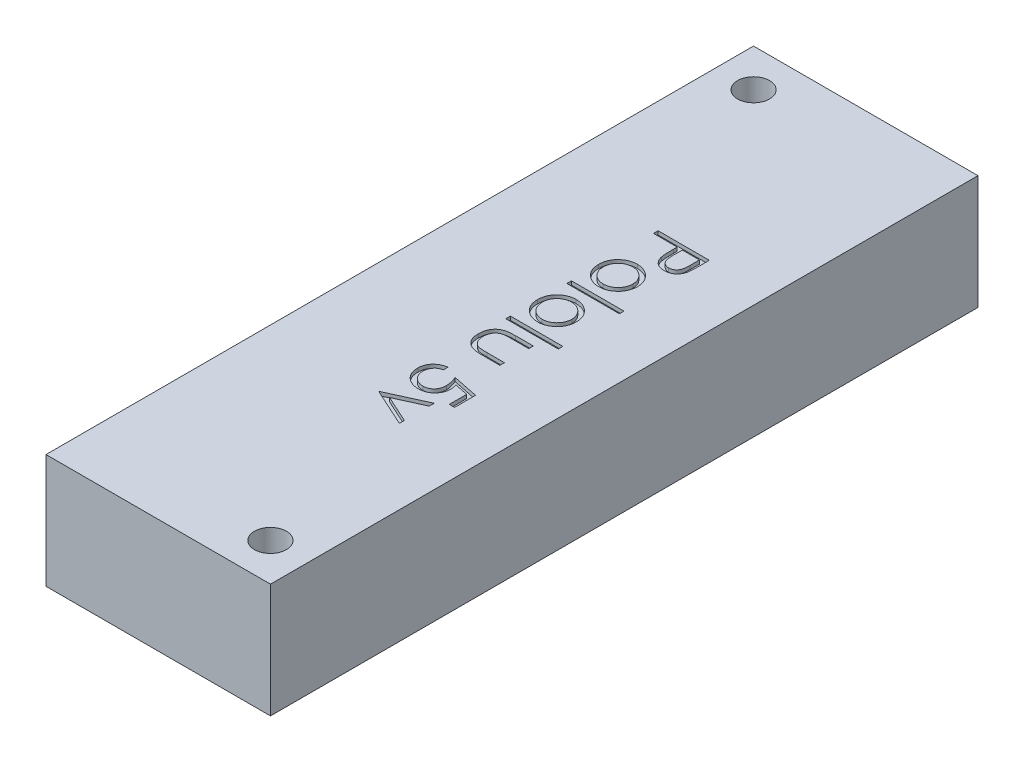
SolidWorks part; units mm, degrees
ref_plane "Front Plane" through (0, 0, 0) normal (0, 0, 1) x (1, 0, 0)
ref_plane "Top Plane" through (0, 0, 0) normal (0, 1, 0) x (1, 0, 0)
ref_plane "Right Plane" through (0, 0, 0) normal (1, 0, 0) x (0, 0, -1)
sketch "Sketch1" plane through (0, 0, 0) normal (0, 1, 0) x (1, 0, 0)
  line L1 (-7.67, -24.175) -> (7.67, -24.175)
  line L2 (-7.67, -24.175) -> (-7.67, 24.175)
  line L3 (-7.67, 24.175) -> (7.67, 24.175)
  line L4 (7.67, -24.175) -> (7.67, 24.175)
  line L5 (-7.67, -24.175) -> (7.67, 24.175) construction
  line L6 (-7.67, 24.175) -> (7.67, -24.175) construction
  point P0 (0, 0)
  dimension "D1" = 15.34
  dimension "D2" = 48.35
extrude "Boss-Extrude1" add sketch "Sketch1" along normal blind 7.8
sketch "Sketch3" plane through (0, 7.8, 0) normal (0, 1, 0) x (1, 0, 0)
  circle A0 centre (0, 21.59) radius 1.0922 construction
  circle A1 centre (0, -21.59) radius 1.0922 construction
  circle A2 centre (-5.08, 21.59) radius 1.0922
  circle A3 centre (5.08, 21.59) radius 1.0922 construction
  circle A4 centre (5.08, -21.59) radius 1.0922
  circle A5 centre (-5.08, -21.59) radius 1.0922 construction
  dimension "D1" = 2.1844
  dimension "D2" = 10.16
  dimension "D3" = 43.18
  dimension "D4" = 21.59
  dimension "D5" = 5.08
extrude "Cut-Extrude1" cut sketch "Sketch3" against normal through all
sketch "Sketch5" plane through (0, 7.8, 0) normal (0, 1, 0) x (1, 0, 0)
  line L1 (0, 24.175) -> (0, -24.175) construction
  line L2 (7.67, 24.175) -> (-7.67, 24.175) construction
  line L3 (-7.67, -24.175) -> (7.67, -24.175) construction
  text T0 "Pololu 5v"
extrude "Cut-Extrude3" cut sketch "Sketch5" against normal blind 0.254
